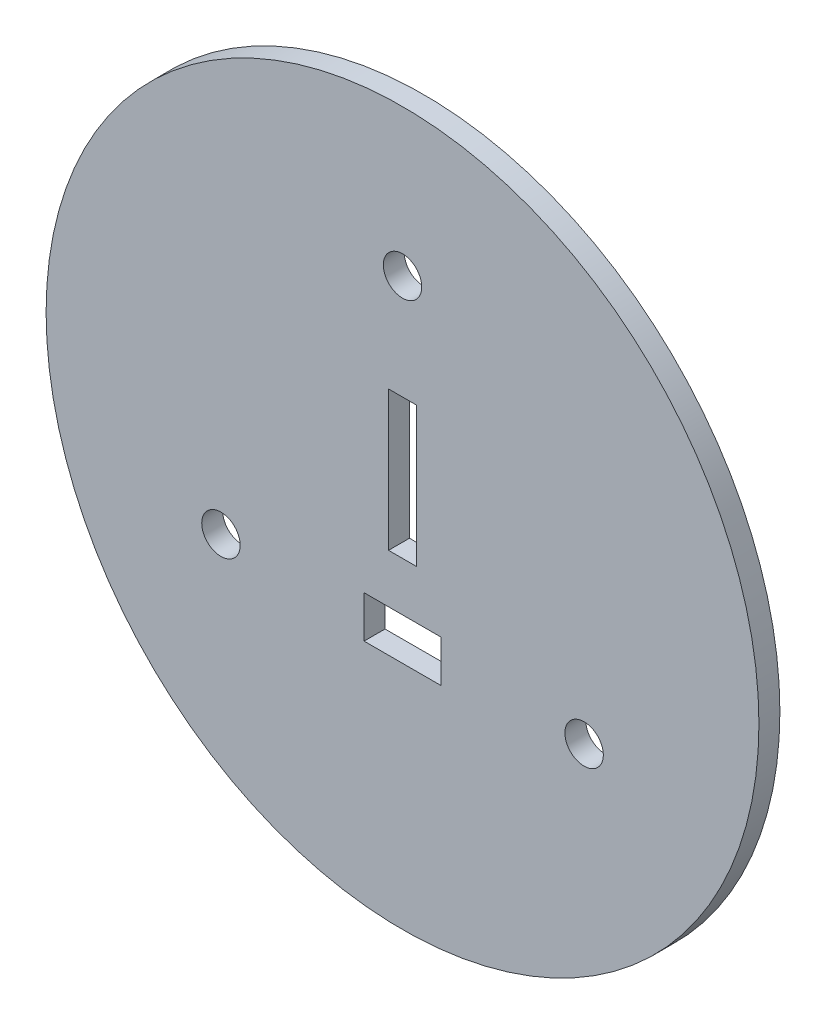
SolidWorks part; units mm, degrees
ref_plane "Спереди" through (0, 0, 0) normal (0, 0, 1) x (1, 0, 0)
ref_plane "Сверху" through (0, 0, 0) normal (0, 1, 0) x (1, 0, 0)
ref_plane "Справа" through (0, 0, 0) normal (1, 0, 0) x (0, 0, -1)
sketch "Эскиз2" plane through (0, 0, 0) normal (0, 0, 1) x (1, 0, 0)
  circle A0 centre (0, 0) radius 51
  dimension "D1" = 102
extrude "Бобышка-Вытянуть1" add sketch "Эскиз2" along normal blind 3
sketch "Эскиз3" plane through (0, 0, 0) normal (0, 0, -1) x (-1, 0, 0)
  circle A0 centre (0, 30) radius 2.75
  dimension "D1" = 5.5
  dimension "D2" = 30
extrude "Вырез-Вытянуть1" cut sketch "Эскиз3" against normal blind 3
pattern_circular "Круговой массив1" count 3 over 360 about axis through (0, 0, 0) along (0, 0, 1) of "Вырез-Вытянуть1"
sketch "Эскиз4" plane through (0, 0, 3) normal (0, 0, 1) x (1, 0, 0)
  line L1 (-2, -5) -> (2, -5)
  line L2 (-2, -5) -> (-2, 15)
  line L3 (-2, 15) -> (2, 15)
  line L4 (2, -5) -> (2, 15)
  line L5 (-2, -5) -> (2, 15) construction
  line L6 (-2, 15) -> (2, -5) construction
  line L7 (-5.5, -18) -> (5.5, -18)
  line L8 (-5.5, -18) -> (-5.5, -12)
  line L9 (-5.5, -12) -> (5.5, -12)
  line L10 (5.5, -18) -> (5.5, -12)
  line L11 (-5.5, -18) -> (5.5, -12) construction
  line L12 (-5.5, -12) -> (5.5, -18) construction
  circle A2 centre (0, 30) radius 2.75
  circle A3 centre (0, 30) radius 2.75
  circle A4 centre (-25.9808, -15) radius 2.75 construction
  point P0 (0, 5)
  point P5 (0, -15)
  dimension "D2" = 4
  dimension "D3" = 20
  dimension "D4" = 11
  dimension "D5" = 6
  dimension "D6" = 15
  dimension "D7" = 3
  dimension "D1" = 0
extrude "Вырез-Вытянуть2" cut sketch "Эскиз4" against normal blind 13.3
